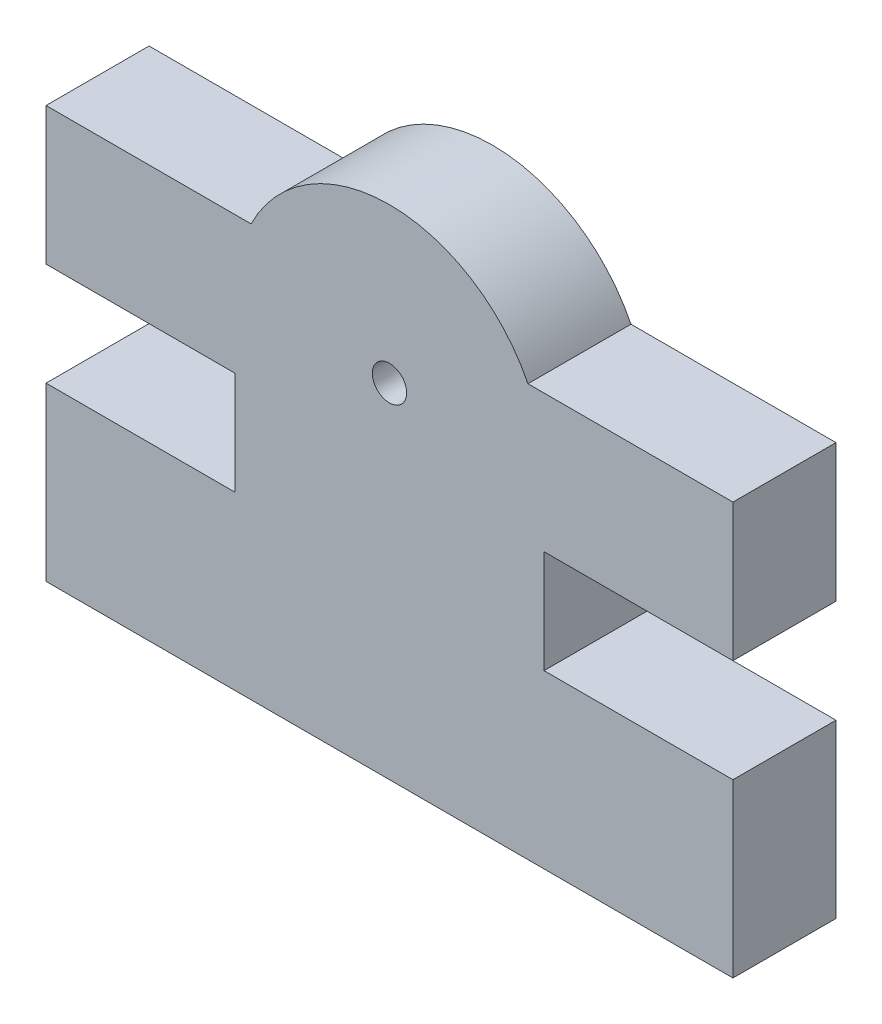
SolidWorks part; units mm, degrees
ref_plane "Front Plane" through (0, 0, 0) normal (0, 0, 1) x (1, 0, 0)
ref_plane "Top Plane" through (0, 0, 0) normal (0, 1, 0) x (1, 0, 0)
ref_plane "Right Plane" through (0, 0, 0) normal (1, 0, 0) x (0, 0, -1)
sketch "Sketch1" plane through (0, 0, 0) normal (0, 0, 1) x (1, 0, 0)
  line L0 (0.4689, 7) -> (-5.5, 7)
  line L1 (0, 0) -> (9, 0)
  line L2 (0, 0) -> (0, 3)
  line L3 (14.5, 7) -> (8.5311, 7)
  line L4 (9, 0) -> (9, 3)
  line L5 (14.5, 7) -> (14.5, 3)
  line L6 (14.5, 3) -> (9, 3)
  line L7 (-5.5, 7) -> (-5.5, 3)
  line L8 (14.5, 7) -> (-5.5, 3) construction
  line L9 (14.5, 3) -> (-5.5, 7) construction
  line L10 (0, 3) -> (-5.5, 3)
  arc A0 (8.5311, 7) -> (0.4689, 7) centre (4.5, 5) ccw
  circle A1 centre (4.5, 5) radius 0.5
  point P7 (4.5, 0)
  dimension "D3" = 1
  dimension "D4" = 4.5
  dimension "D1" = 9
  dimension "D2" = 5.9689
  dimension "D5" = 3
  dimension "D6" = 4
  dimension "D7" = 20
extrude "Boss-Extrude1" add sketch "Sketch1" along normal blind 3
sketch "Sketch2" plane through (0, 0, 0) normal (0, -1, 0) x (1, 0, 0)
  line L0 (4.5, 0) -> (4.5, 3) construction
  line L1 (-5.5, 3) -> (14.5, 3)
  line L2 (-5.5, 3) -> (-5.5, 0)
  line L3 (-5.5, 0) -> (14.5, 0)
  line L4 (14.5, 3) -> (14.5, 0)
  line L5 (-5.5, 3) -> (14.5, 0) construction
  line L6 (-5.5, 0) -> (14.5, 3) construction
  line L7 (0, 0) -> (9, 0) construction
  point P0 (4.5, 1.5)
  point P9 (4.5, 0)
  dimension "D1" = 20
extrude "Boss-Extrude2" add sketch "Sketch2" along normal blind 5
